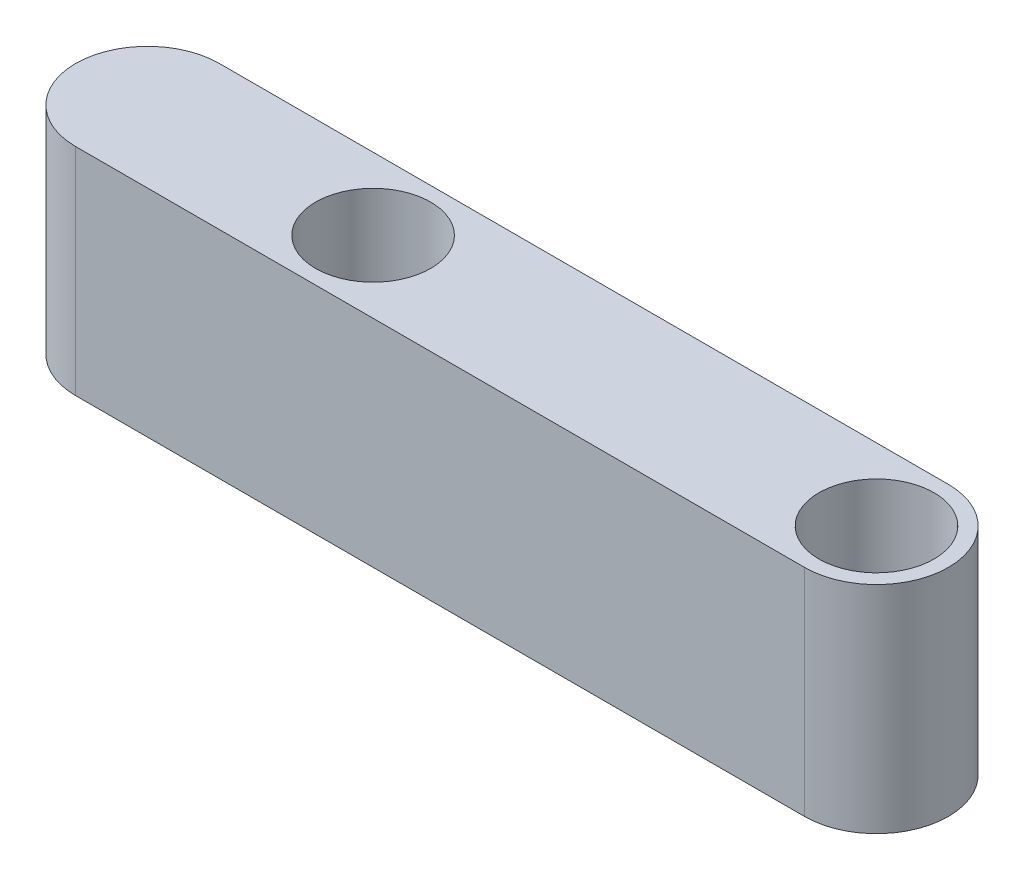
SolidWorks part; units mm, degrees
ref_plane "Front Plane" through (0, 0, 0) normal (0, 0, 1) x (1, 0, 0)
ref_plane "Top Plane" through (0, 0, 0) normal (0, 1, 0) x (1, 0, 0)
ref_plane "Right Plane" through (0, 0, 0) normal (1, 0, 0) x (0, 0, -1)
sketch "Sketch1" plane through (0, 0, 0) normal (0, 1, 0) x (1, 0, 0)
  line L0 (-49.5532, 32.2621) -> (-43.4616, 32.2621) construction
  line L1 (-49.5532, 32.7621) -> (-43.4616, 32.7621)
  line L2 (-49.5532, 31.7621) -> (-43.4616, 31.7621)
  line L3 (-49.5532, 32.2621) -> (-46.5074, 32.2621)
  line L5 (-48.0303, 32.2621) -> (-47.0532, 32.2621)
  line L6 (-48.0303, 32.2621) -> (-48.5303, 32.2621) construction
  line L7 (-48.0303, 31.7621) -> (-48.5303, 31.7621)
  line L8 (-48.0303, 32.7621) -> (-48.5303, 32.7621)
  line L10 (-43.4616, 32.2621) -> (-46.9616, 32.2621)
  arc A0 (-49.5532, 32.7621) -> (-49.5532, 31.7621) centre (-49.5532, 32.2621) ccw
  arc A1 (-43.4616, 31.7621) -> (-43.4616, 32.7621) centre (-43.4616, 32.2621) ccw
  circle A4 centre (-43.4616, 32.2621) radius 0.4
  arc A6 (-48.0303, 31.7621) -> (-48.0303, 32.7621) centre (-48.0303, 32.2621) ccw
  arc A7 (-48.5303, 32.7621) -> (-48.5303, 31.7621) centre (-48.5303, 32.2621) ccw
  circle A8 centre (-46.9616, 32.2621) radius 0.4
  point P2 (-46.5074, 32.2621)
  point P13 (-48.2803, 32.2621)
extrude "Boss-Extrude1" add sketch "Sketch1" along normal blind 1.5
